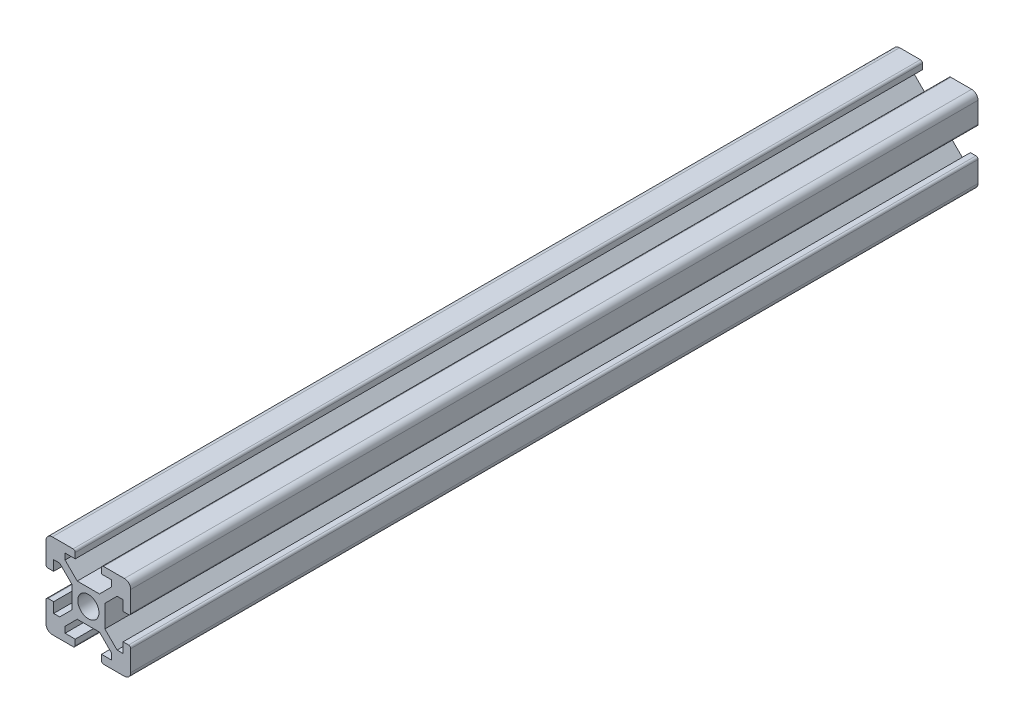
SolidWorks part; units mm, degrees
ref_plane "前视基准面" through (0, 0, 0) normal (0, 0, 1) x (1, 0, 0)
ref_plane "上视基准面" through (0, 0, 0) normal (0, 1, 0) x (1, 0, 0)
ref_plane "右视基准面" through (0, 0, 0) normal (1, 0, 0) x (0, 0, -1)
sketch "草图1" plane through (0, 0, 0) normal (0, 0, 1) x (1, 0, 0)
  line L0 (0, 6.9) -> (0, 0)
  line L1 (20, 20) -> (20, 13.1)
  line L2 (1.8, 15.5) -> (3.2272, 15.5)
  line L3 (4.5, 16.7728) -> (4.5, 18.2)
  line L4 (0, 13.1) -> (0, 20)
  line L5 (6.9, 20) -> (6.9, 18.2)
  line L6 (6.9, 18.2) -> (4.5, 18.2)
  line L7 (13.1, 20) -> (20, 20)
  line L8 (6.9, 20) -> (0, 20)
  line L9 (0, 0) -> (6.9, 0)
  line L10 (13.1, 0) -> (20, 0)
  line L11 (15.5, 18.2) -> (15.5, 16.7728)
  line L12 (16.7728, 15.5) -> (18.2, 15.5)
  line L13 (20, 6.9) -> (20, 0)
  line L14 (1.8, 4.5) -> (3.2272, 4.5)
  line L15 (4.5, 3.2272) -> (4.5, 1.8)
  line L16 (12.6272, 6.1) -> (15.5, 3.2272)
  line L17 (18.2, 4.5) -> (16.7728, 4.5)
  line L18 (15.5, 3.2272) -> (15.5, 1.8)
  line L19 (13.9, 7.3728) -> (16.7728, 4.5)
  line L20 (13.1, 20) -> (13.1, 18.2)
  line L21 (13.1, 18.2) -> (15.5, 18.2)
  line L22 (7.3728, 13.9) -> (12.6272, 13.9)
  line L23 (13.9, 12.6272) -> (13.9, 7.3728)
  line L24 (7.3728, 6.1) -> (12.6272, 6.1)
  line L25 (6.1, 12.6272) -> (6.1, 7.3728)
  line L27 (12.6272, 13.9) -> (15.5, 16.7728)
  line L30 (3.2272, 4.5) -> (6.1, 7.3728)
  line L32 (4.5, 3.2272) -> (7.3728, 6.1)
  line L33 (20, 13.1) -> (18.2, 13.1)
  line L34 (18.2, 13.1) -> (18.2, 15.5)
  line L36 (20, 6.9) -> (18.2, 6.9)
  line L37 (18.2, 6.9) -> (18.2, 4.5)
  line L39 (13.1, 0) -> (13.1, 1.8)
  line L40 (13.1, 1.8) -> (15.5, 1.8)
  line L42 (6.9, 0) -> (6.9, 1.8)
  line L43 (6.9, 1.8) -> (4.5, 1.8)
  line L45 (0, 6.9) -> (1.8, 6.9)
  line L46 (1.8, 6.9) -> (1.8, 4.5)
  line L48 (0, 13.1) -> (1.8, 13.1)
  line L49 (1.8, 13.1) -> (1.8, 15.5)
  line L50 (4.5, 16.7728) -> (7.3728, 13.9)
  line L51 (3.2272, 15.5) -> (6.1, 12.6272)
  line L53 (13.9, 12.6272) -> (16.7728, 15.5)
  line L62 (1.8, 13.1) -> (1.8, 15.5)
  line L63 (0, 13.1) -> (1.8, 13.1)
  line L66 (6.9, 18.2) -> (4.5, 18.2)
  line L67 (6.9, 20) -> (6.9, 18.2)
  line L68 (3.2272, 15.5) -> (1.8, 15.5)
  line L69 (4.5, 18.2) -> (4.5, 16.7728)
  line L75 (4.5, 1.8) -> (4.5, 3.2272)
  line L76 (3.2272, 4.5) -> (1.8, 4.5)
  line L77 (6.9, 0) -> (6.9, 1.8)
  line L78 (6.9, 1.8) -> (4.5, 1.8)
  line L80 (0, 6.9) -> (1.8, 6.9)
  line L81 (1.8, 6.9) -> (1.8, 4.5)
  line L90 (1.8, 6.9) -> (1.8, 4.5)
  line L91 (0, 6.9) -> (1.8, 6.9)
  line L93 (18.2, 6.9) -> (18.2, 4.5)
  line L94 (20, 6.9) -> (18.2, 6.9)
  line L98 (13.1, 1.8) -> (15.5, 1.8)
  line L99 (13.1, 0) -> (13.1, 1.8)
  line L100 (16.7728, 4.5) -> (18.2, 4.5)
  line L101 (15.5, 1.8) -> (15.5, 3.2272)
  line L106 (6.9, 1.8) -> (4.5, 1.8)
  line L107 (6.9, 0) -> (6.9, 1.8)
  line L109 (4.5, 3.2272) -> (4.5, 1.8)
  line L110 (1.8, 4.5) -> (3.2272, 4.5)
  circle A0 centre (10, 10) radius 2.5
extrude "凸台-拉伸1" add sketch "草图1" along normal blind 200 contours L23 L53 L12 L34 L33 L1 L7 L20 L21 L11 L27 L22 L50 L3 L6 L5 L8 L4 L48 L49 L2 L51 L25 L30 L14 L46 L45 L0 L9 L42 L43 L15 L32 L24 L16 L18 L40 L39 L10 L13 L36 L37 L17 L19
fillet "圆角1" radius 1.5 1 edges at (20, 20, 100)
fillet "圆角2" radius 1.5 1 edges at (0, 20, 100)
fillet "圆角3" radius 1.5 1 edges at (0, 0, 100)
fillet "圆角4" radius 1.5 1 edges at (20, 0, 100)
fillet "圆角5" radius 0.5 1 edges at (13.1, 20, 100)
fillet "圆角6" radius 0.5 1 edges at (6.9, 20, 100)
fillet "圆角7" radius 0.5 1 edges at (0, 13.1, 100)
fillet "圆角8" radius 0.5 1 edges at (0, 6.9, 100)
fillet "圆角9" radius 0.5 1 edges at (6.9, 0, 100)
fillet "圆角10" radius 0.5 1 edges at (13.1, 0, 100)
fillet "圆角11" radius 0.5 1 edges at (20, 13.1, 100)
fillet "圆角12" radius 0.5 1 edges at (20, 6.9, 100)
